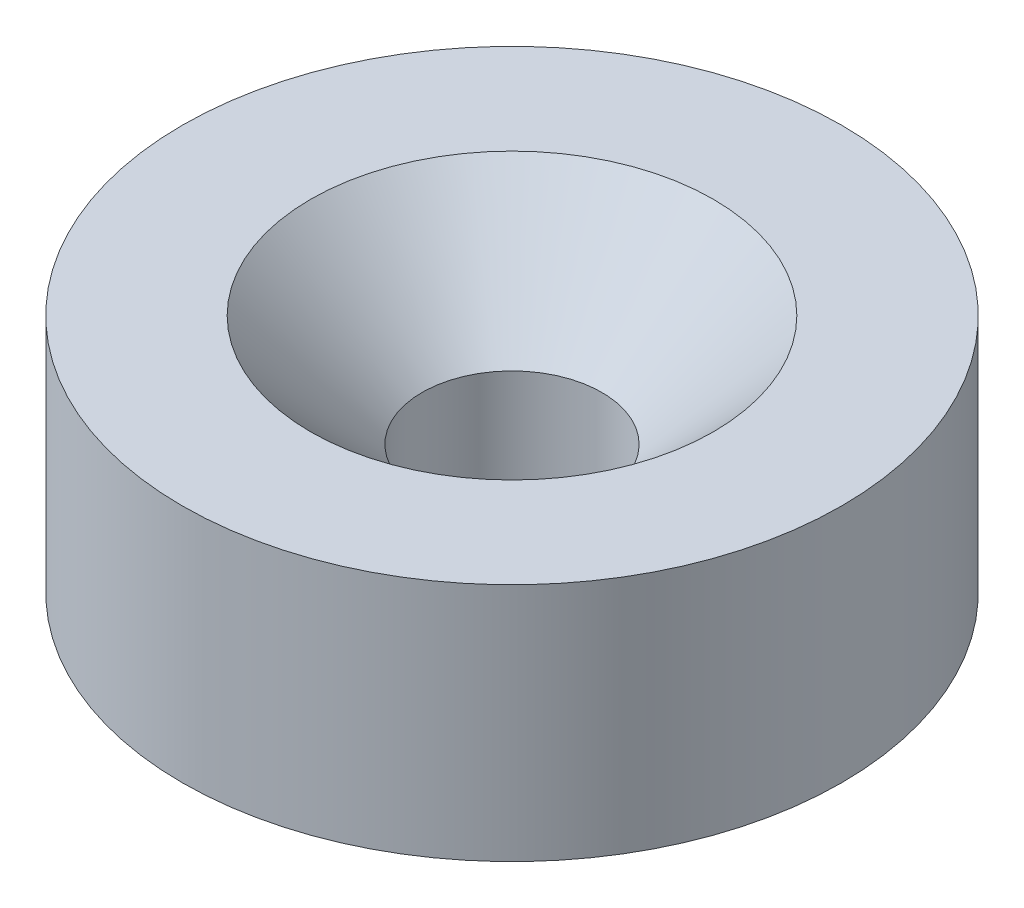
SolidWorks part; units mm, degrees
ref_plane "Front Plane" through (0, 0, 0) normal (0, 0, 1) x (1, 0, 0)
ref_plane "Top Plane" through (0, 0, 0) normal (0, 1, 0) x (1, 0, 0)
ref_plane "Right Plane" through (0, 0, 0) normal (1, 0, 0) x (0, 0, -1)
sketch "Sketch2" plane through (0, 0, 0) normal (0, 1, 0) x (1, 0, 0)
  circle A0 centre (0, 0) radius 5.5
  dimension "D1" = 11
extrude "Boss-Extrude1" add sketch "Sketch2" along normal blind 4
hole_wizard "CSK for M3 SFHCS1" positions "Sketch3" profile "Sketch4" countersink size "M3" standard "ANSI Metric"
sketch "Sketch3" plane through (0, 4, 0) normal (0, 1, 0) x (1, 0, 0)
  point P0 (0, 0)
sketch "Sketch4" plane through (0, 4, 0) normal (1, 0, 0) x (0, 0, 1)
  line L0 (0, 0) -> (0, 32)
  line L1 (0, 32) -> (1.5, 31.0987)
  line L2 (1.5, 31.0987) -> (1.5, 1.86)
  line L3 (1.5, 1.86) -> (3.36, 0)
  line L5 (3.36, 0) -> (0, 0)
  line L6 (-1.5, 1.86) -> (-3.36, 0) construction
  line L10 (0, 32) -> (-1.5, 31.0987) construction
  line L11 (0, -6.35) -> (0, 107.95) construction
  dimension "Hole Dia." = 3
  dimension "Hole Depth" = 32
  dimension "Near C'Sink Dia." = 6.72
  dimension "Near C'Sink Angle" = 90
  dimension "Drill Angle" = 118
